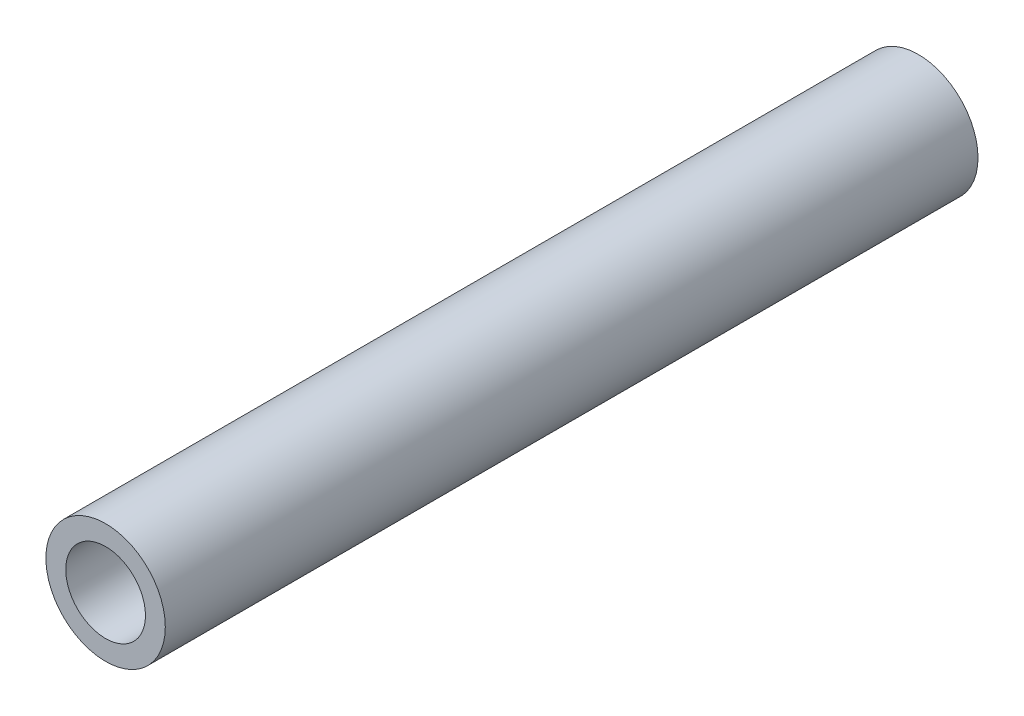
SolidWorks part; units mm, degrees
material "Alloy Steel"
ref_plane "Front Plane" through (0, 0, 0) normal (0, 0, 1) x (1, 0, 0)
ref_plane "Top Plane" through (0, 0, 0) normal (0, 1, 0) x (1, 0, 0)
ref_plane "Right Plane" through (0, 0, 0) normal (1, 0, 0) x (0, 0, -1)
sketch "Sketch1" plane through (0, 0, 0) normal (0, 0, 1) x (1, 0, 0)
  circle A0 centre (0, 0) radius 11.9062
  circle A1 centre (0, 0) radius 7.9502
  dimension "D1" = 15.9004
  dimension "D2" = 23.8125
extrude "Boss-Extrude1" add sketch "Sketch1" along normal blind 162.052
